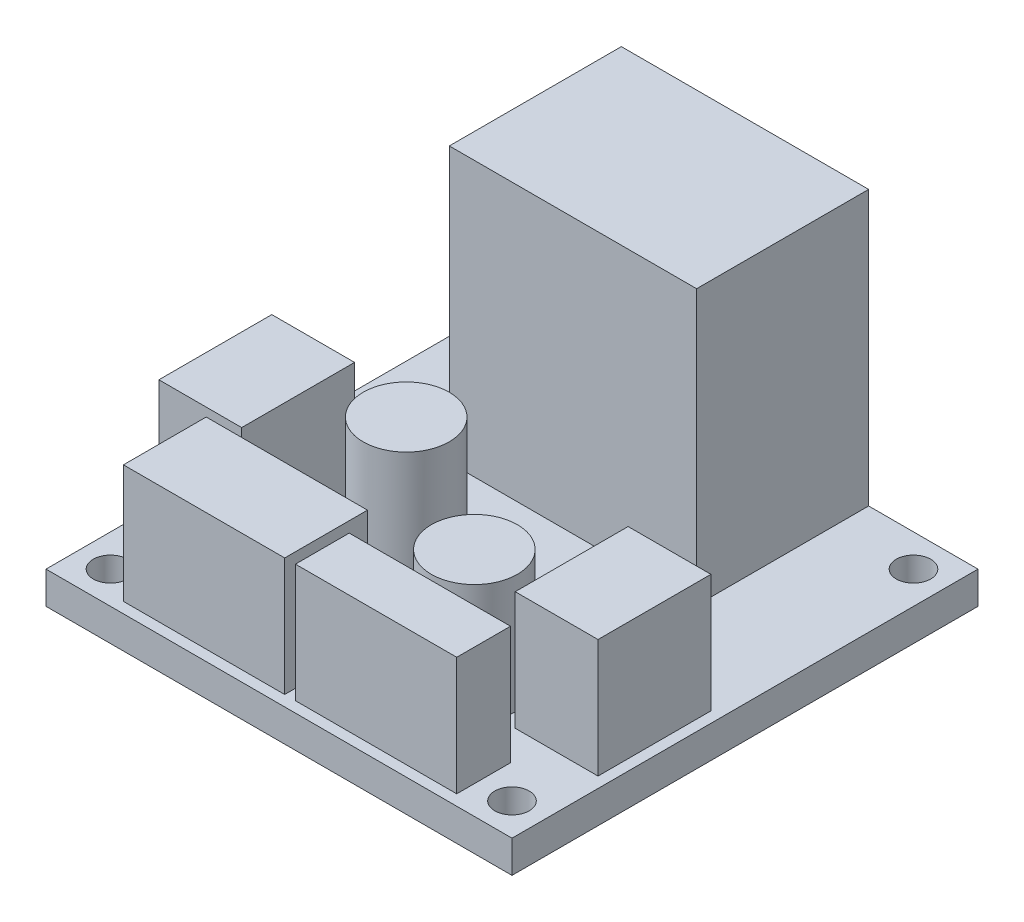
SolidWorks part; units mm, degrees
ref_plane "정면" through (0, 0, 0) normal (0, 0, 1) x (1, 0, 0)
ref_plane "윗면" through (0, 0, 0) normal (0, 1, 0) x (1, 0, 0)
ref_plane "우측면" through (0, 0, 0) normal (1, 0, 0) x (0, 0, -1)
sketch "스케치1" plane through (0, 0, 0) normal (0, 1, 0) x (1, 0, 0)
  line L1 (-21.67, -21.67) -> (21.67, -21.67)
  line L2 (-21.67, -21.67) -> (-21.67, 21.67)
  line L3 (-21.67, 21.67) -> (21.67, 21.67)
  line L4 (21.67, -21.67) -> (21.67, 21.67)
  line L5 (-21.67, -21.67) -> (21.67, 21.67) construction
  line L6 (-21.67, 21.67) -> (21.67, -21.67) construction
  point P0 (0, 0)
  dimension "D1" = 43.34
extrude "보스-돌출1" add sketch "스케치1" along normal blind 28.5
sketch "스케치2" plane through (0, 28.5, 0) normal (0, 1, 0) x (1, 0, 0)
  line L4 (0, 21.67) -> (0, 5.67) construction
  line L6 (-11.5, 21.67) -> (-11.5, 5.67)
  line L7 (-11.5, 5.67) -> (11.5, 5.67)
  line L8 (21.67, -21.67) -> (21.67, 21.67)
  line L9 (21.67, 21.67) -> (-21.67, 21.67)
  line L10 (-21.67, 21.67) -> (-21.67, -21.67)
  line L11 (-21.67, -21.67) -> (21.67, -21.67)
  line L12 (21.67, -21.67) -> (21.67, 21.67)
  line L13 (21.67, 21.67) -> (11.5, 21.67)
  line L14 (-21.67, 21.67) -> (-21.67, -21.67)
  line L15 (-21.67, -21.67) -> (21.67, -21.67)
  line L16 (11.5, 21.67) -> (11.5, 5.67)
  line L17 (-11.5, 21.67) -> (-21.67, 21.67)
  dimension "D2" = 23
  dimension "D3" = 16
  dimension "D1" = 0
extrude "컷-돌출1" cut sketch "스케치2" against normal offset from surface (25.5 mm away) 3 up to face at (0, 0, 0)
sketch "스케치3" plane through (0, 3, 0) normal (0, 1, 0) x (1, 0, 0)
  line L0 (21.67, -21.67) -> (21.67, 21.67) construction
  line L1 (-20.67, -1.67) -> (-12.97, -1.67)
  line L2 (-20.67, -1.67) -> (-20.67, -12.17)
  line L3 (-20.67, -12.17) -> (-12.97, -12.17)
  line L4 (-12.97, -1.67) -> (-12.97, -12.17)
  line L5 (-15.47, -12.97) -> (-0.47, -12.97)
  line L6 (-15.47, -12.97) -> (-15.47, -20.67)
  line L7 (-15.47, -20.67) -> (-0.47, -20.67)
  line L8 (-0.47, -12.97) -> (-0.47, -20.67)
  line L9 (0.53, -15.67) -> (15.53, -15.67)
  line L10 (0.53, -15.67) -> (0.53, -20.67)
  line L11 (0.53, -20.67) -> (15.53, -20.67)
  line L12 (15.53, -15.67) -> (15.53, -20.67)
  line L13 (12.97, -2.17) -> (20.67, -2.17)
  line L14 (12.97, -2.17) -> (12.97, -12.67)
  line L15 (12.97, -12.67) -> (20.67, -12.67)
  line L16 (20.67, -2.17) -> (20.67, -12.67)
  line L17 (-21.67, -21.67) -> (21.67, -21.67) construction
  line L18 (-21.67, 21.67) -> (-21.67, -21.67) construction
  circle A0 centre (-6.17, -3.67) radius 4
  circle A1 centre (7.67, -11.17) radius 4
  dimension "D1" = 8
  dimension "D2" = 14
  dimension "D3" = 10.5
  dimension "D4" = 18
  dimension "D5" = 15.5
  dimension "D6" = 10.5
  dimension "D7" = 1
  dimension "D8" = 9
  dimension "D9" = 7.7
  dimension "D10" = 1
  dimension "D11" = 9.5
  dimension "D12" = 15
  dimension "D13" = 7.7
  dimension "D14" = 1
  dimension "D15" = 6.2
  dimension "D16" = 5
  dimension "D17" = 1
  dimension "D18" = 15
extrude "보스-돌출2" add sketch "스케치3" along normal blind 11
sketch "스케치4" plane through (0, 3, 0) normal (0, 1, 0) x (1, 0, 0)
  line L0 (-11.5, 21.67) -> (-21.67, 21.67) construction
  line L1 (-21.67, 21.67) -> (-21.67, -21.67) construction
  circle A0 centre (-18.67, 18.67) radius 1.6
  circle A1 centre (18.67, 18.67) radius 1.6
  circle A2 centre (18.67, -18.67) radius 1.6
  circle A3 centre (-18.67, -18.67) radius 1.6
  point P15 (0, 0)
  dimension "D1" = 3.2
  dimension "D2" = 3
  dimension "D3" = 3
  dimension "D4" = 4
extrude "컷-돌출2" cut sketch "스케치4" against normal through all
